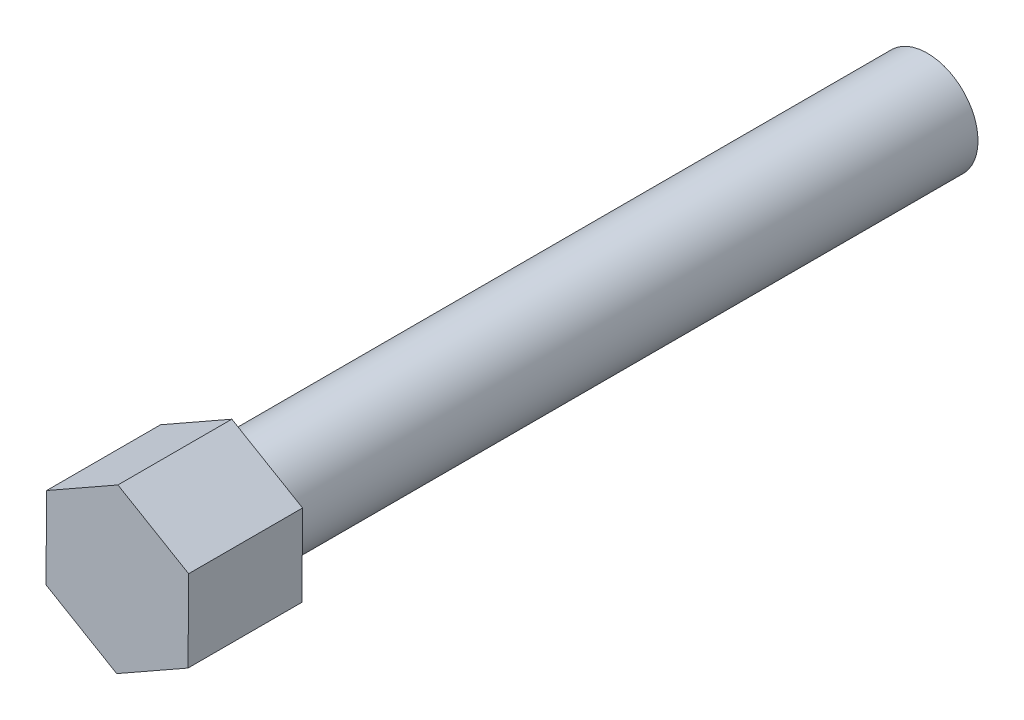
SolidWorks part; units mm, degrees
ref_plane "前视基准面" through (0, 0, 0) normal (0, 0, 1) x (1, 0, 0)
ref_plane "上视基准面" through (0, 0, 0) normal (0, 1, 0) x (1, 0, 0)
ref_plane "右视基准面" through (0, 0, 0) normal (1, 0, 0) x (0, 0, -1)
sketch "草图1" plane through (0, 0, 0) normal (0, 0, 1) x (1, 0, 0)
  circle A0 centre (0, 0) radius 4
  dimension "D1" = 8
extrude "拉伸1" add sketch "草图1" along normal blind 55
sketch "草图2" plane through (0, 0, 55) normal (0, 0, 1) x (1, 0, 0)
  line L1 (-5.5872, 3.2805) -> (-5.6346, -3.1984)
  line L2 (-5.6346, -3.1984) -> (-0.0474, -6.4789)
  line L3 (-0.0474, -6.4789) -> (5.5872, -3.2805)
  line L4 (5.5872, -3.2805) -> (5.6346, 3.1984)
  line L5 (5.6346, 3.1984) -> (0.0474, 6.4789)
  line L6 (0.0474, 6.4789) -> (-5.5872, 3.2805)
  circle A0 centre (0, 0) radius 5.6111 construction
extrude "拉伸2" add sketch "草图2" along normal blind 9
